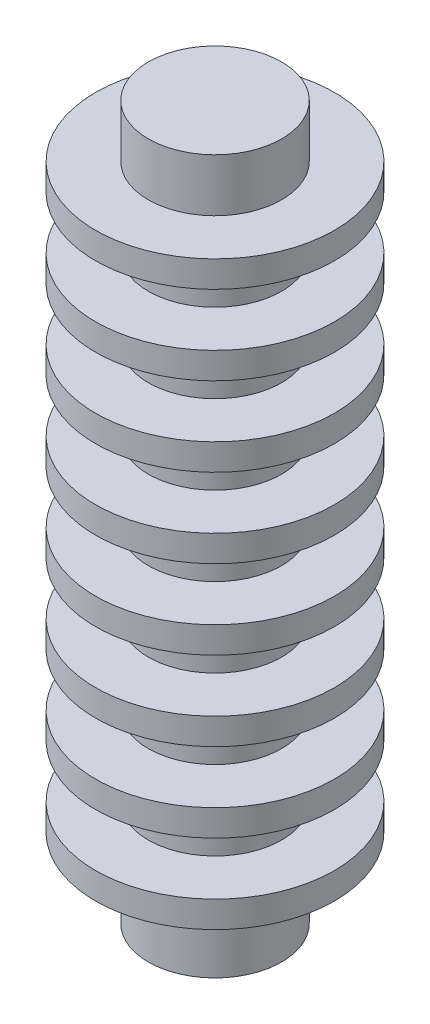
SolidWorks part; units mm, degrees
ref_plane "Front Plane" through (0, 0, 0) normal (0, 0, 1) x (1, 0, 0)
ref_plane "Top Plane" through (0, 0, 0) normal (0, 1, 0) x (1, 0, 0)
ref_plane "Right Plane" through (0, 0, 0) normal (1, 0, 0) x (0, 0, -1)
sketch "Sketch1" plane through (0, 0, 0) normal (0, 0, 1) x (1, 0, 0)
  line L0 (0, -24) -> (0, 24) construction
  line L1 (5.05, 24) -> (5.05, 23)
  line L2 (-18.6825, 24) -> (5.05, 24) construction
  line L3 (5.05, 18) -> (5.05, 17)
  line L4 (5.05, 17) -> (9.05, 17)
  line L5 (5.05, 23) -> (9.05, 23)
  line L6 (9.05, 23) -> (9.05, 21)
  line L7 (9.05, 21) -> (5.05, 21)
  line L8 (5.05, 21) -> (5.05, 18)
  line L9 (5.05, 24) -> (5.05, 27)
  line L10 (5.05, 27) -> (0, 27)
  line L11 (5.05, -24) -> (5.05, -27)
  line L12 (5.05, -27) -> (0, -27)
  line L13 (9.05, 17) -> (9.05, 15)
  line L14 (9.05, 15) -> (5.05, 15)
  line L15 (5.05, 15) -> (5.05, 12)
  line L16 (0, 27) -> (0, -27)
  line L20 (5.05, 12) -> (5.05, 11)
  line L21 (5.05, 11) -> (9.05, 11)
  line L22 (9.05, 11) -> (9.05, 9)
  line L23 (9.05, 9) -> (5.05, 9)
  line L24 (5.05, 9) -> (5.05, 6)
  line L29 (5.05, 6) -> (5.05, 5)
  line L30 (5.05, 5) -> (9.05, 5)
  line L31 (9.05, 5) -> (9.05, 3)
  line L32 (9.05, 3) -> (5.05, 3)
  line L33 (5.05, 3) -> (5.05, 0)
  line L38 (5.05, 0) -> (5.05, -1)
  line L39 (5.05, -1) -> (9.05, -1)
  line L40 (9.05, -1) -> (9.05, -3)
  line L41 (9.05, -3) -> (5.05, -3)
  line L42 (5.05, -3) -> (5.05, -6)
  line L47 (5.05, -6) -> (5.05, -7)
  line L48 (5.05, -7) -> (9.05, -7)
  line L49 (9.05, -7) -> (9.05, -9)
  line L50 (9.05, -9) -> (5.05, -9)
  line L51 (5.05, -9) -> (5.05, -12)
  line L56 (5.05, -12) -> (5.05, -13)
  line L57 (5.05, -13) -> (9.05, -13)
  line L58 (9.05, -13) -> (9.05, -15)
  line L59 (9.05, -15) -> (5.05, -15)
  line L60 (5.05, -15) -> (5.05, -18)
  line L65 (5.05, -18) -> (5.05, -19)
  line L66 (5.05, -19) -> (9.05, -19)
  line L67 (9.05, -19) -> (9.05, -21)
  line L68 (9.05, -21) -> (5.05, -21)
  line L69 (5.05, -21) -> (5.05, -24)
  point P4 (0, 0)
  dimension "D1" = 48
  dimension "D2" = 5.05
  dimension "D3" = 3
  dimension "D4" = 3
  dimension "D7" = 2
  dimension "D11" = 4
  dimension "D12" = 8
revolve "Revolve1" add sketch "Sketch1" angle 360 about L16
